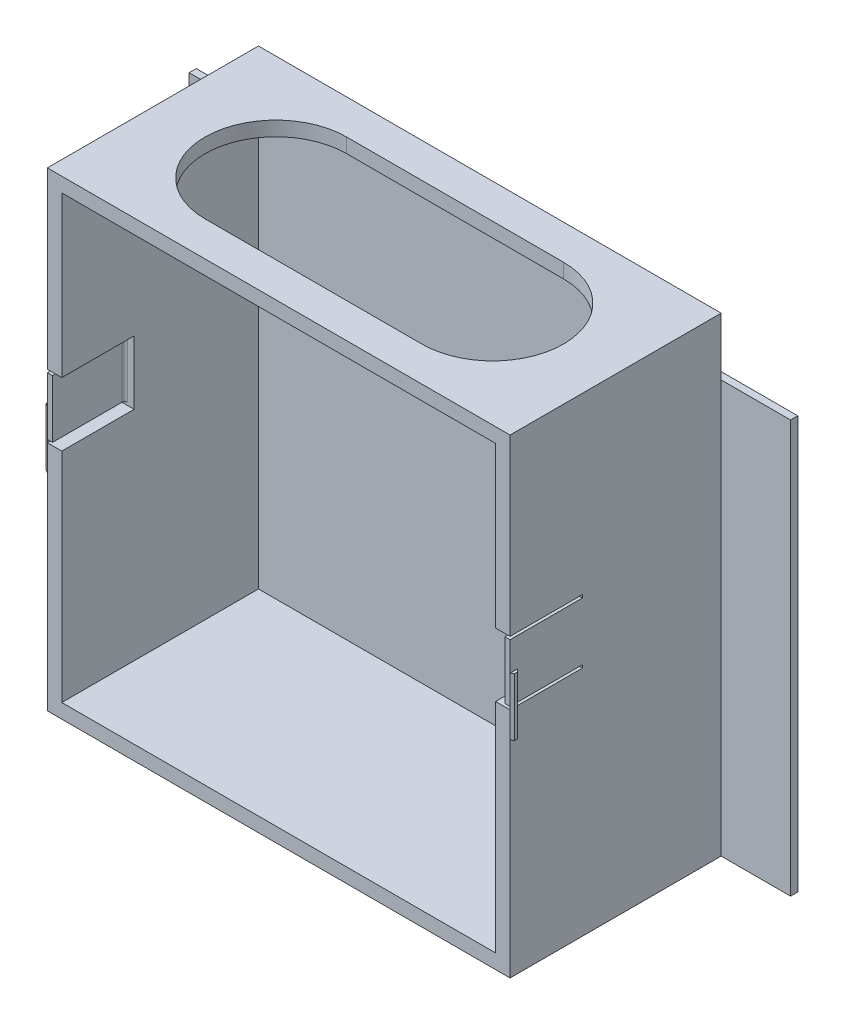
SolidWorks part; units mm, degrees
ref_plane "Front Plane" through (0, 0, 0) normal (0, 0, 1) x (1, 0, 0)
ref_plane "Top Plane" through (0, 0, 0) normal (0, 1, 0) x (1, 0, 0)
ref_plane "Right Plane" through (0, 0, 0) normal (1, 0, 0) x (0, 0, -1)
sketch "Sketch2" plane through (0, 0, 0) normal (0, 1, 0) x (1, 0, 0)
  line L1 (-101.6, -46.355) -> (101.6, -46.355)
  line L2 (-101.6, -46.355) -> (-101.6, 46.355)
  line L3 (-101.6, 46.355) -> (101.6, 46.355)
  line L4 (101.6, -46.355) -> (101.6, 46.355)
  line L5 (-101.6, -46.355) -> (101.6, 46.355) construction
  line L6 (-101.6, 46.355) -> (101.6, -46.355) construction
  point P0 (0, 0)
  dimension "D1" = 203.2
  dimension "D2" = 92.71
extrude "Boss-Extrude1" add sketch "Sketch2" along normal blind 206.502
sketch "Sketch3" plane through (0, 0, 46.355) normal (0, 0, 1) x (1, 0, 0)
  line L0 (-95.25, 6.35) -> (95.25, 6.35)
  line L1 (95.25, 6.35) -> (95.25, 200.152)
  line L2 (95.25, 200.152) -> (-95.25, 200.152)
  line L3 (-95.25, 200.152) -> (-95.25, 6.35)
  line L4 (-101.6, 0) -> (101.6, 0)
  line L5 (101.6, 0) -> (101.6, 206.502)
  line L6 (101.6, 206.502) -> (-101.6, 206.502)
  line L7 (-101.6, 206.502) -> (-101.6, 0)
  line L8 (-101.6, 0) -> (101.6, 0) construction
  line L9 (101.6, 0) -> (101.6, 206.502) construction
  line L10 (101.6, 206.502) -> (-101.6, 206.502) construction
  line L11 (-101.6, 206.502) -> (-101.6, 0) construction
  dimension "D1" = 0
  dimension "D2" = 6.35
extrude "Cut-Extrude1" cut sketch "Sketch3" against normal blind 86.36 contours L3 L0 L1 L2
sketch "Sketch5" plane through (0, 206.502, 0) normal (0, -1, 0) x (1, 0, 0)
  line L0 (-47.625, 0) -> (47.625, 0) construction
  line L1 (-47.625, 31.115) -> (47.625, 31.115)
  line L2 (-47.625, -31.115) -> (47.625, -31.115)
  arc A0 (-47.625, 31.115) -> (-47.625, -31.115) centre (-47.625, 0) ccw
  arc A1 (47.625, -31.115) -> (47.625, 31.115) centre (47.625, 0) ccw
  point P2 (0, 0)
  dimension "D1" = 31.115
  dimension "D2" = 95.25
extrude "Cut-Extrude2" cut sketch "Sketch5" along normal up to next contours A1 L1 A0 L2
sketch "Sketch6" plane through (0, 0, -46.355) normal (0, 0, -1) x (-1, 0, 0)
  line L0 (-101.6, 206.502) -> (-101.6, 0) construction
  line L1 (-132.08, 181.102) -> (132.08, 181.102)
  line L2 (-132.08, 181.102) -> (-132.08, 0)
  line L3 (-132.08, 0) -> (132.08, 0)
  line L4 (132.08, 181.102) -> (132.08, 0)
  line L5 (101.6, 206.502) -> (101.6, 0) construction
  dimension "D1" = 30.48
  dimension "D2" = 30.48
extrude "Boss-Extrude2" add sketch "Sketch6" along normal blind 3.175
sketch "Sketch8" plane through (0, 0, 46.355) normal (0, 0, 1) x (1, 0, 0)
  line L0 (-101.6, 206.502) -> (-101.6, 0) construction
  line L1 (-99.314, 128.651) -> (-95.25, 128.651)
  line L2 (-99.314, 128.651) -> (-99.314, 103.251)
  line L3 (-99.314, 103.251) -> (-95.25, 103.251)
  line L4 (-95.25, 128.651) -> (-95.25, 103.251)
  line L6 (-101.6, 206.502) -> (101.6, 206.502) construction
  line L8 (-101.6, 181.102) -> (-101.6, 0) construction
  line L9 (-95.25, 128.651) -> (-101.6, 128.651)
  line L10 (-95.25, 128.651) -> (-95.25, 129.921)
  line L11 (-95.25, 129.921) -> (-101.6, 129.921)
  line L12 (-101.6, 128.651) -> (-101.6, 129.921)
  line L14 (-95.25, 103.251) -> (-101.6, 103.251)
  line L15 (-95.25, 103.251) -> (-95.25, 101.981)
  line L16 (-95.25, 101.981) -> (-101.6, 101.981)
  line L17 (-101.6, 103.251) -> (-101.6, 101.981)
  line M3 (-95.25, 6.35) -> (-95.25, 200.152)
  line M10 (-101.6, 206.502) -> (-101.6, 0)
  dimension "D1" = 2.286
  dimension "D2" = 4.064
  dimension "D3" = 25.4
  dimension "D4" = 77.851
  dimension "D5" = 1.27
  dimension "D6" = 1.27
extrude "Cut-Extrude3" cut sketch "Sketch8" against normal blind 31.75 contours L2 L3 L1 M3 | L16 L3 L14 M3 M10 | L10 L11 L12 L9
fillet "Fillet1" radius 1.27 1 edges at (-99.314, 115.951, 14.605)
ref_plane "Plane1" through (0, 103.251, 0) normal (0, -1, 0) x (-1, 0, 0)
sketch "Sketch10" plane through (0, 103.251, 0) normal (0, -1, 0) x (-1, 0, 0)
  line L0 (101.6, -46.355) -> (102.8077, -45.6577)
  line L1 (101.6, 46.355) -> (101.6, -46.355) construction
  line L2 (102.8077, -45.6577) -> (102.8077, -44.3877)
  line L3 (102.8077, -44.3877) -> (101.6, -43.18)
  line L4 (102.8077, -45.0227) -> (102.3823, -45.0227) construction
  line L5 (101.6, -46.355) -> (101.6, -43.18)
  dimension "D1" = 30
  dimension "D2" = 45
  dimension "D3" = 1.27
  dimension "D4" = 3.175
extrude "Boss-Extrude3" add sketch "Sketch10" along normal blind 12.7 and the other way blind 12.7 contours L0 L2 L3 L5
ref_plane "Plane2" through (0, 0, 0) normal (1, 0, 0) x (0, 0, -1)
mirror "Mirror1" about plane through (0, 0, 0) normal (1, 0, 0) of "Boss-Extrude3", "Fillet1", "Cut-Extrude3"
